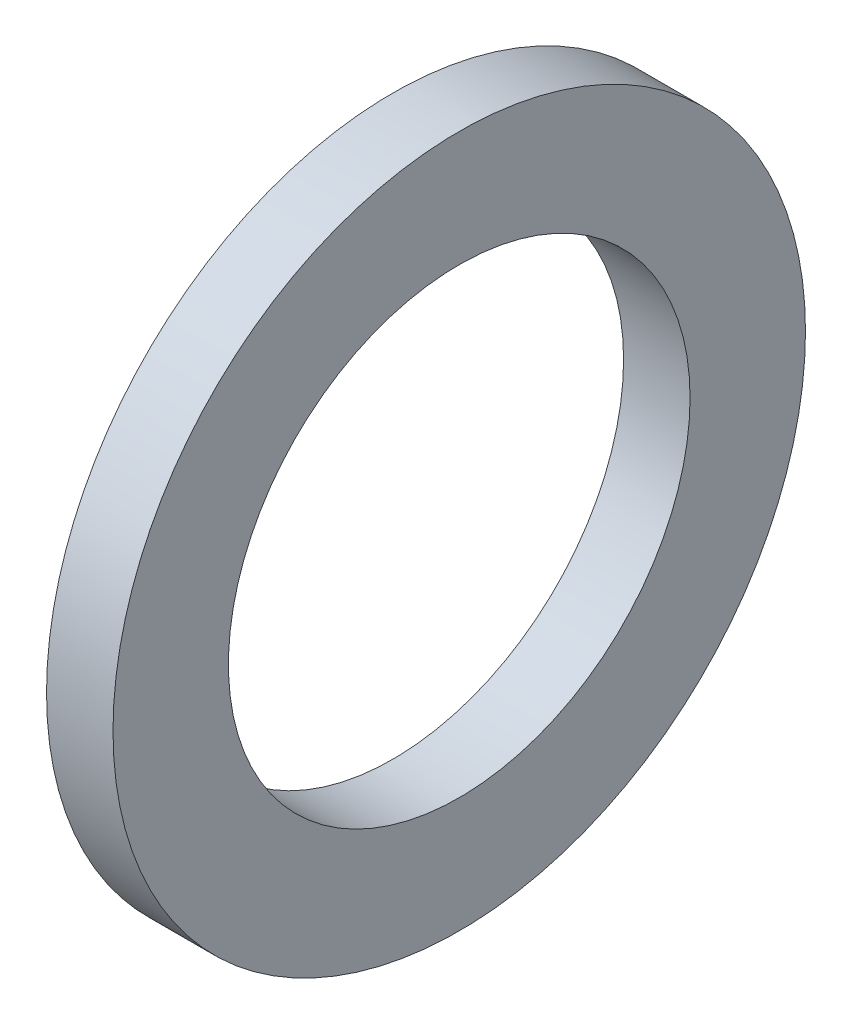
SolidWorks part; units mm, degrees
material "Nylon 101"
ref_plane "Front Plane" through (0, 0, 0) normal (0, 0, 1) x (1, 0, 0)
ref_plane "Top Plane" through (0, 0, 0) normal (0, 1, 0) x (1, 0, 0)
ref_plane "Right Plane" through (0, 0, 0) normal (1, 0, 0) x (0, 0, -1)
sketch "Sketch1" plane through (0, 0, 0) normal (1, 0, 0) x (0, 0, -1)
  circle A0 centre (0, 0) radius 4.7625
  circle A1 centre (0, 0) radius 3.175
  dimension "OD" = 9.525
  dimension "ID" = 6.35
extrude "Boss-Extrude1" add sketch "Sketch1" along normal blind 0.9144
